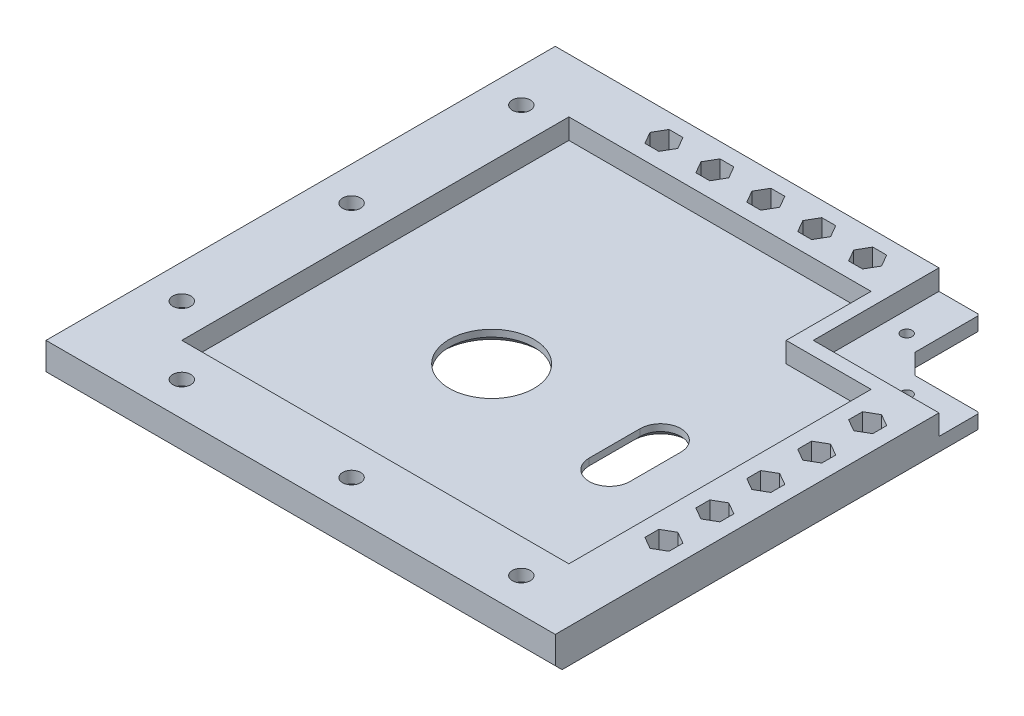
SolidWorks part; units mm, degrees
ref_plane "Front Plane" through (0, 0, 0) normal (0, 0, 1) x (1, 0, 0)
ref_plane "Top Plane" through (0, 0, 0) normal (0, 1, 0) x (1, 0, 0)
ref_plane "Right Plane" through (0, 0, 0) normal (1, 0, 0) x (0, 0, -1)
sketch "Sketch1" plane through (0, 0, 0) normal (0, 1, 0) x (1, 0, 0)
  line L0 (110, 150) -> (110, 142) construction
  line L1 (0, 0) -> (150, 0)
  line L2 (0, 0) -> (0, 150)
  line L3 (0, 150) -> (150, 150)
  line L4 (150, 0) -> (150, 150)
  line L5 (150, 150) -> (110, 150) construction
  line L6 (150, 150) -> (150, 110) construction
  line L7 (150, 110) -> (110, 110) construction
  line L8 (110, 150) -> (110, 110) construction
  line L9 (110, 142) -> (100, 142) construction
  line L10 (10, 10) -> (10, 30) construction
  line L11 (110, 110) -> (142, 110) construction
  line L12 (110, 110) -> (110, 142) construction
  line L13 (110, 142) -> (142, 142) construction
  line L14 (142, 110) -> (142, 142) construction
  line L15 (0, 0) -> (10, 0) construction
  line L16 (0, 0) -> (0, 10) construction
  line L17 (0, 10) -> (10, 10) construction
  line L18 (10, 0) -> (10, 10) construction
  line L19 (10, 30) -> (10, 80) construction
  line L20 (10, 80) -> (10, 130) construction
  line L21 (10, 10) -> (19.3806, 10) construction
  line L22 (10, 10) -> (30, 10) construction
  line L27 (0, 20) -> (150, 20) [skipped]
  line L28 (150, 20) -> (150, -130) [skipped]
  line L29 (0, -130) -> (150, -130) [skipped]
  line L30 (0, 20) -> (0, -130) [skipped]
  circle A0 centre (100, 142) radius 2.15
  circle A1 centre (85, 142) radius 2.15
  circle A2 centre (70, 142) radius 2.15
  circle A3 centre (55, 142) radius 2.15
  circle A4 centre (40, 142) radius 2.15
  circle A5 centre (142, 40) radius 2.15
  circle A6 centre (142, 55) radius 2.15
  circle A7 centre (142, 70) radius 2.15
  circle A8 centre (142, 85) radius 2.15
  circle A9 centre (142, 100) radius 2.15
  circle A10 centre (10, 30) radius 2.65
  circle A11 centre (10, 80) radius 2.65
  circle A12 centre (10, 130) radius 2.65
  circle A13 centre (30, 10) radius 2.65
  circle A14 centre (80, 10) radius 2.65
  circle A15 centre (130, 10) radius 2.65
  point P34 (142, 142)
  point P55 (10, 10)
  dimension "D5" = 8
  dimension "D7" = 4.3
  dimension "D15" = 2
  dimension "D1" = 150
  dimension "D2" = 150
  dimension "D3" = 40
  dimension "D4" = 40
  dimension "D6" = 10
  dimension "D9" = 2
  dimension "D10" = 10
  dimension "D11" = 10
  dimension "D12" = 20
  dimension "D13" = 50
  dimension "D14" = 50
  dimension "D8" = 5
extrude "Boss-Extrude1" add sketch "Sketch1" along normal blind 4
sketch "Sketch2" plane through (0, 4, 0) normal (0, 1, 0) x (1, 0, 0)
  line L1 (0, 150) -> (20, 150)
  line L2 (0, 150) -> (0, 0)
  line L4 (20, 134) -> (20, 20)
  line L5 (150, 0) -> (150, 150) construction
  line L6 (150, 0) -> (0, 0)
  line L7 (150, 0) -> (150, 20)
  line L8 (134, 20) -> (20, 20)
  line L10 (20, 150) -> (150, 150)
  line L12 (20, 134) -> (109, 134)
  line L13 (150, 150) -> (150, 134)
  line L14 (59.0992, 142) -> (57.0496, 145.55)
  line L16 (150, 20) -> (150, 134)
  line L18 (134, 20) -> (134, 109)
  line L19 (44.0992, 142) -> (42.0496, 145.55)
  line L20 (42.0496, 145.55) -> (37.9504, 145.55)
  line L21 (37.9504, 145.55) -> (35.9008, 142)
  line L22 (35.9008, 142) -> (37.9504, 138.45)
  line L23 (37.9504, 138.45) -> (42.0496, 138.45)
  line L24 (42.0496, 138.45) -> (44.0992, 142)
  line L25 (57.0496, 145.55) -> (52.9504, 145.55)
  line L26 (52.9504, 145.55) -> (50.9008, 142)
  line L27 (50.9008, 142) -> (52.9504, 138.45)
  line L28 (52.9504, 138.45) -> (57.0496, 138.45)
  line L29 (57.0496, 138.45) -> (59.0992, 142)
  line L30 (74.0992, 142) -> (72.0496, 145.55)
  line L31 (72.0496, 145.55) -> (67.9504, 145.55)
  line L32 (67.9504, 145.55) -> (65.9008, 142)
  line L33 (65.9008, 142) -> (67.9504, 138.45)
  line L34 (67.9504, 138.45) -> (72.0496, 138.45)
  line L35 (72.0496, 138.45) -> (74.0992, 142)
  line L36 (89.0992, 142) -> (87.0496, 145.55)
  line L37 (87.0496, 145.55) -> (82.9504, 145.55)
  line L38 (82.9504, 145.55) -> (80.9008, 142)
  line L39 (80.9008, 142) -> (82.9504, 138.45)
  line L40 (82.9504, 138.45) -> (87.0496, 138.45)
  line L41 (87.0496, 138.45) -> (89.0992, 142)
  line L42 (104.0992, 142) -> (102.0496, 145.55)
  line L43 (102.0496, 145.55) -> (97.9504, 145.55)
  line L44 (97.9504, 145.55) -> (95.9008, 142)
  line L45 (95.9008, 142) -> (97.9504, 138.45)
  line L46 (97.9504, 138.45) -> (102.0496, 138.45)
  line L47 (102.0496, 138.45) -> (104.0992, 142)
  line L48 (142, 80.9008) -> (145.55, 82.9504)
  line L49 (142, 95.9008) -> (145.55, 97.9504)
  line L50 (145.55, 97.9504) -> (145.55, 102.0496)
  line L51 (145.55, 102.0496) -> (142, 104.0992)
  line L52 (142, 104.0992) -> (138.45, 102.0496)
  line L53 (138.45, 102.0496) -> (138.45, 97.9504)
  line L54 (138.45, 97.9504) -> (142, 95.9008)
  line L55 (145.55, 82.9504) -> (145.55, 87.0496)
  line L56 (145.55, 87.0496) -> (142, 89.0992)
  line L57 (142, 89.0992) -> (138.45, 87.0496)
  line L58 (138.45, 87.0496) -> (138.45, 82.9504)
  line L59 (138.45, 82.9504) -> (142, 80.9008)
  line L60 (142, 65.9008) -> (145.55, 67.9504)
  line L61 (145.55, 67.9504) -> (145.55, 72.0496)
  line L62 (145.55, 72.0496) -> (142, 74.0992)
  line L63 (142, 74.0992) -> (138.45, 72.0496)
  line L64 (138.45, 72.0496) -> (138.45, 67.9504)
  line L65 (138.45, 67.9504) -> (142, 65.9008)
  line L66 (142, 50.9008) -> (145.55, 52.9504)
  line L67 (145.55, 52.9504) -> (145.55, 57.0496)
  line L68 (145.55, 57.0496) -> (142, 59.0992)
  line L69 (142, 59.0992) -> (138.45, 57.0496)
  line L70 (138.45, 57.0496) -> (138.45, 52.9504)
  line L71 (138.45, 52.9504) -> (142, 50.9008)
  line L72 (142, 35.9008) -> (145.55, 37.9504)
  line L73 (145.55, 37.9504) -> (145.55, 42.0496)
  line L74 (145.55, 42.0496) -> (142, 44.0992)
  line L75 (142, 44.0992) -> (138.45, 42.0496)
  line L76 (138.45, 42.0496) -> (138.45, 37.9504)
  line L77 (138.45, 37.9504) -> (142, 35.9008)
  line L81 (134, 109) -> (109, 109)
  line L82 (109, 134) -> (109, 109)
  circle A0 centre (10, 130) radius 2.65
  circle A1 centre (10, 80) radius 2.65
  circle A2 centre (10, 30) radius 2.65
  circle A3 centre (30, 10) radius 2.65
  circle A4 centre (80, 10) radius 2.65
  circle A5 centre (130, 10) radius 2.65
  circle A6 centre (40, 142) radius 3.55 construction
  circle A7 centre (142, 100) radius 3.55 construction
  dimension "D3" = 16
  dimension "D5" = 7.1
  dimension "D7" = 7.1
  dimension "D1" = 20
  dimension "D2" = 20
  dimension "D4" = 16
  dimension "D9" = 25
  dimension "D10" = 25
  dimension "D6" = 5
  dimension "D8" = 5
extrude "Boss-Extrude2" add sketch "Sketch2" along normal blind 6
sketch "Sketch3" plane through (0, 0, 0) normal (0, -1, 0) x (1, 0, 0)
  line L0 (93.75, -93.75) -> (37.5, -37.5) construction
  line L1 (37.5, -37.5) -> (93.75, -93.75) construction
  line L2 (93.75, -93.75) -> (37.5, -37.5) construction
  circle A0 centre (10, -130) radius 4.5
  circle A1 centre (10, -80) radius 4.5
  circle A2 centre (10, -30) radius 4.5
  circle A3 centre (30, -10) radius 4.5
  circle A4 centre (80, -10) radius 4.5
  circle A5 centre (130, -10) radius 4.5
  circle A6 centre (65.625, -65.625) radius 12.5
extrude "Cut-Extrude1" cut sketch "Sketch3" against normal blind 6.5
sketch "Sketch4" plane through (0, 10, 0) normal (0, 1, 0) x (1, 0, 0)
  line L1 (150, 150) -> (125, 150)
  line L2 (150, 150) -> (150, 125)
  line L3 (150, 125) -> (125, 125)
  line L4 (125, 150) -> (125, 125)
  dimension "D1" = 25
  dimension "D2" = 25
extrude "Cut-Extrude2" cut sketch "Sketch4" against normal up to surface (10 mm away) up to face at (10, 0, -134.5)
sketch "Sketch5" plane through (0, 10, 0) normal (0, 1, 0) x (1, 0, 0)
  line L1 (125, 125) -> (150, 125) construction
  line L2 (125, 125) -> (125, 150) construction
  line L3 (125, 150) -> (150, 150) construction
  line L4 (150, 125) -> (150, 150) construction
  line L5 (150, 150) -> (113, 150)
  line L6 (150, 150) -> (150, 113)
  line L7 (150, 113) -> (113, 113)
  line L8 (113, 150) -> (113, 113)
  dimension "D1" = 25
  dimension "D2" = 25
  dimension "D3" = 37
  dimension "D4" = 37
extrude "Cut-Extrude3" cut sketch "Sketch5" against normal up to surface (6 mm away) up to face at (65.625, 4, -78.125)
sketch "Sketch6" plane through (0, 4, 0) normal (0, 1, 0) x (1, 0, 0)
  line L0 (113, 113) -> (125, 125) construction
  line L1 (125, 125) -> (150, 125) construction
  line L2 (125, 125) -> (119, 119) construction
  line L3 (119, 119) -> (119, 150) construction
  line L4 (125, 150) -> (113, 150) construction
  line L5 (119, 119) -> (150, 119) construction
  line L6 (150, 113) -> (150, 125) construction
  circle A0 centre (119, 134.5) radius 1.6
  circle A1 centre (134.5, 119) radius 1.6
extrude "Cut-Extrude4" cut sketch "Sketch6" against normal blind 24.5
chamfer "Chamfer1" distance 2 angle 45 2 edges at (75, 0, 0) (0, 0, -75)
sketch "Sketch7" plane through (0, 0, 0) normal (0, -1, 0) x (1, 0, 0)
  line L0 (150, -63.5) -> (110, -63.5) construction
  line L1 (150, -2) -> (150, -125) construction
  line L2 (110, -71) -> (110, -56) construction
  line L3 (104, -71) -> (104, -56)
  line L4 (116, -71) -> (116, -56)
  arc A0 (104, -71) -> (116, -71) centre (110, -71) ccw
  arc A1 (116, -56) -> (104, -56) centre (110, -56) ccw
  point P6 (110, -63.5)
  dimension "D3" = 6
  dimension "D1" = 40
  dimension "D2" = 15
extrude "Cut-Extrude5" cut sketch "Sketch7" against normal blind 24.5
chamfer "Chamfer2" distance 2 angle 45 5 edges at (65.625, 0, -78.125) (110, 0, -50) (104, 0, -63.5) (116, 0, -63.5) (110, 0, -77)
chamfer "Chamfer3" distance 0.5 angle 45 2 edges at (150, 2, -125) (125, 2, -150)
chamfer "Chamfer4" distance 6 angle 45 1 edges at (125, 2, -125)
